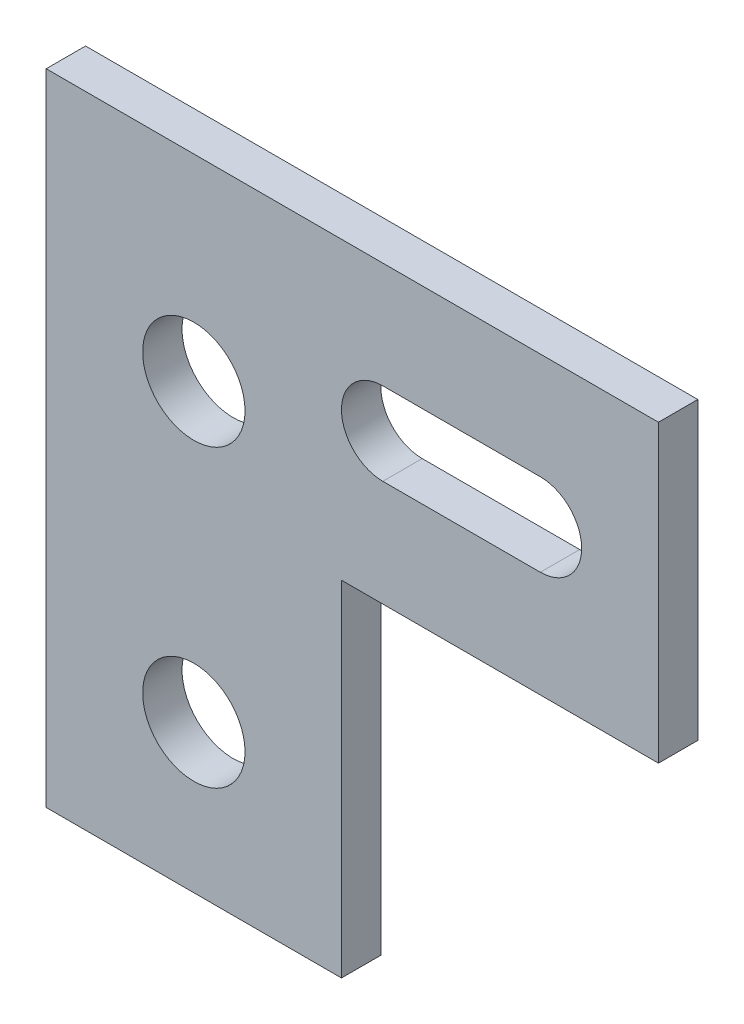
SolidWorks part; units mm, degrees
ref_plane "前视基准面" through (0, 0, 0) normal (0, 0, 1) x (1, 0, 0)
ref_plane "上视基准面" through (0, 0, 0) normal (0, 1, 0) x (1, 0, 0)
ref_plane "右视基准面" through (0, 0, 0) normal (1, 0, 0) x (0, 0, -1)
other "Configuration Table"
sketch "草图1" plane through (0, 0, 0) normal (0, 0, 1) x (1, 0, 0)
  line L0 (0, 0) -> (0, 17.5)
  line L1 (0, 17.5) -> (31.1, 17.5)
  line L2 (31.1, 17.5) -> (31.1, 2.5)
  line L4 (15, 0) -> (15, -15)
  line L5 (15, -15) -> (0, -15)
  line L6 (0, -15) -> (0, 0)
  line L7 (17.1, 10) -> (25.1, 10) construction
  line L10 (15, 0) -> (-17.0909, 0) construction
  line L11 (7.5, -15) -> (7.5, -22.0531) construction
  line L12 (15, 0) -> (-10.7717, 0)
  line L13 (17.1, 12.1) -> (25.1, 12.1)
  line L14 (17.1, 7.9) -> (25.1, 7.9)
  line L15 (15, 0) -> (15, 2.5)
  line L16 (15, 2.5) -> (31.1, 2.5)
  circle A2 centre (7.5, 7.5) radius 2.6
  circle A3 centre (7.5, -7.5) radius 2.6
  arc A4 (17.1, 12.1) -> (17.1, 7.9) centre (17.1, 10) ccw
  arc A5 (25.1, 7.9) -> (25.1, 12.1) centre (25.1, 10) ccw
  point P10 (21.1, 10)
  dimension "D3" = 15
  dimension "D7" = 5.2
  dimension "D4" = 6
  dimension "D5" = 2.1
  dimension "D1" = 15
  dimension "D2" = 8
  dimension "D6" = 15
extrude "凸台-拉伸1" add sketch "草图1" along normal blind 2
